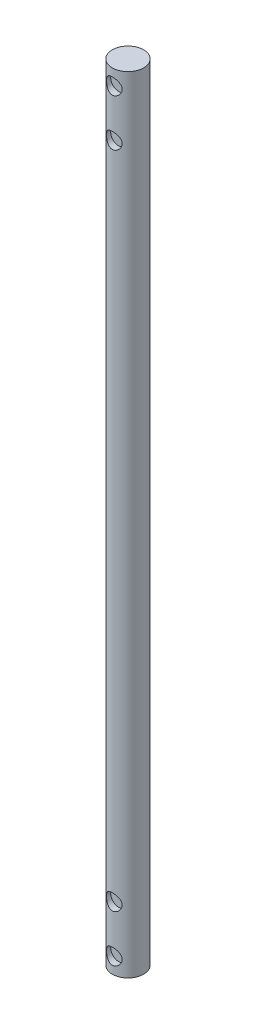
SolidWorks part; units mm, degrees
ref_plane "Front Plane" through (0, 0, 0) normal (0, 0, 1) x (1, 0, 0)
ref_plane "Top Plane" through (0, 0, 0) normal (0, 1, 0) x (1, 0, 0)
ref_plane "Right Plane" through (0, 0, 0) normal (1, 0, 0) x (0, 0, -1)
sketch "Sketch1" plane through (0, 0, 0) normal (0, 1, 0) x (1, 0, 0)
  circle A0 centre (0, 0) radius 5
extrude "Boss-Extrude1" add sketch "Sketch1" along normal blind 250
sketch "Sketch5" plane through (0, 0, 0) normal (0, 0, 1) x (1, 0, 0)
  line L0 (5, 250) -> (-5, 250) construction
  line L1 (0, 182.5074) -> (0, 156.4117) construction
  line L2 (0, 0) -> (0, 66.8413) construction
  line L3 (-6.7676, 0) -> (5.369, 0) construction
  circle A0 centre (0, 5) radius 2.5
  circle A1 centre (0, 20) radius 2.5
  circle A2 centre (0, 245) radius 2.5
  circle A3 centre (0, 230) radius 2.5
  point P0 (0, 5)
  point P1 (0, 20)
  point P16 (0, 245)
  dimension "D2" = 5
  dimension "D4" = 5
  dimension "D6" = 5
  dimension "D7" = 5
  dimension "D8" = 5
  dimension "D1" = 5
  dimension "D3" = 20
  dimension "D5" = 15
extrude "Cut-Extrude1" cut sketch "Sketch5" against normal blind 2 from offset 5
